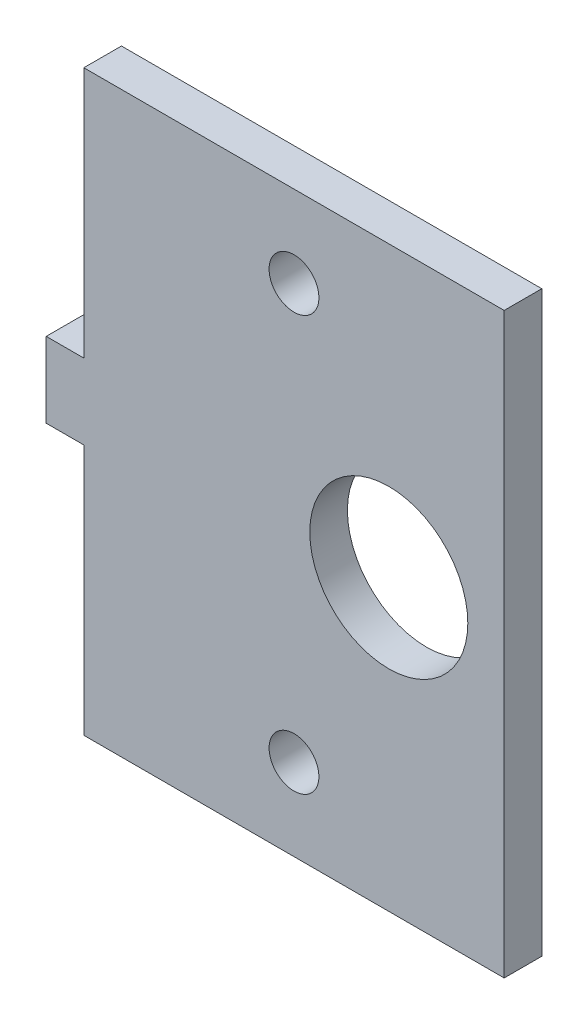
SolidWorks part; units mm, degrees
ref_plane "Front Plane" through (0, 0, 0) normal (0, 0, 1) x (1, 0, 0)
ref_plane "Top Plane" through (0, 0, 0) normal (0, 1, 0) x (1, 0, 0)
ref_plane "Right Plane" through (0, 0, 0) normal (1, 0, 0) x (0, 0, -1)
sketch "Sketch1" plane through (0, 0, 0) normal (0, 0, 1) x (1, 0, 0)
  line L1 (-17.7361, 24.3948) -> (17.7361, 24.3948)
  line L2 (-17.7361, 24.3948) -> (-17.7361, -24.3948)
  line L3 (-17.7361, -24.3948) -> (17.7361, -24.3948)
  line L4 (17.7361, 24.3948) -> (17.7361, -24.3948)
  line L5 (-17.7361, 24.3948) -> (17.7361, -24.3948) construction
  line L6 (-17.7361, -24.3948) -> (17.7361, 24.3948) construction
  point P0 (0, 0)
  point P5 (0, 0)
  point P6 (0, 0)
  point P7 (0, 0)
  dimension "D1" = 35.4721
  dimension "D2" = 48.7897
extrude "Boss-Extrude1" add sketch "Sketch1" along normal blind 3.175
sketch "Sketch2" plane through (0, 0, 0) normal (0, 0, -1) x (-1, 0, 0)
  line L0 (17.7361, -24.3948) -> (-17.7361, -24.3948) construction
  line L1 (-17.7361, -24.3948) -> (-17.7361, 24.3948) construction
  line L2 (-17.7361, 24.3948) -> (17.7361, 24.3948) construction
  circle A0 centre (0, 17.5) radius 2.1018
  circle A1 centre (0, -17.5) radius 2.1019
  circle A2 centre (-8, 0) radius 6.6675
  dimension "D1" = 13.335
  dimension "D2" = 4.2037
  dimension "D3" = 4.2037
  dimension "D4" = 6.8948
  dimension "D5" = 17.7361
  dimension "D6" = 9.7361
  dimension "D7" = 24.3948
  dimension "D8" = 6.8948
  dimension "D9" = 17.7361
extrude "Cut-Extrude1" cut sketch "Sketch2" against normal through all
sketch "Sketch3" plane through (-17.7361, 0, 0) normal (-1, 0, 0) x (0, 0, 1)
  line L0 (0, 0) -> (0, -3.175)
  line L1 (0, 24.3948) -> (0, -24.3948) construction
  line L2 (0, -3.175) -> (3.175, -3.175)
  line L3 (3.175, 24.3948) -> (3.175, -24.3948) construction
  line L4 (3.175, -3.175) -> (3.175, 3.175)
  line L5 (3.175, 3.175) -> (0, 3.175)
  line L6 (0, 3.175) -> (0, 0)
  dimension "D1" = 6.35
extrude "Boss-Extrude2" add sketch "Sketch3" along normal blind 3.175
